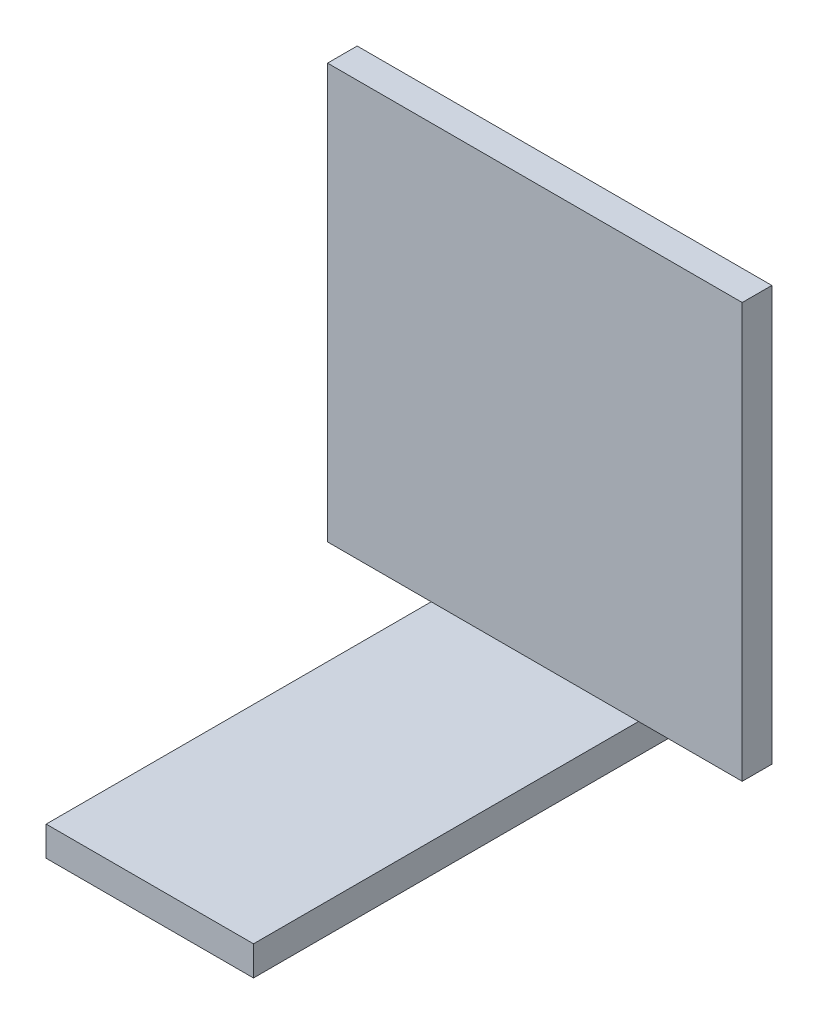
SolidWorks part; units mm, degrees
ref_plane "Front Plane" through (0, 0, 0) normal (0, 0, 1) x (1, 0, 0)
ref_plane "Top Plane" through (0, 0, 0) normal (0, 1, 0) x (1, 0, 0)
ref_plane "Right Plane" through (0, 0, 0) normal (1, 0, 0) x (0, 0, -1)
sketch "Sketch1" plane through (0, 0, 0) normal (0, 1, 0) x (1, 0, 0)
  line L1 (0, 0) -> (35, 0)
  line L2 (0, 0) -> (0, 70)
  line L3 (0, 70) -> (35, 70)
  line L4 (35, 0) -> (35, 70)
  dimension "D1" = 70
  dimension "D2" = 35
extrude "Boss-Extrude1" add sketch "Sketch1" along normal blind 5
sketch "Sketch2" plane through (0, 5, 0) normal (0, 1, 0) x (1, 0, 0)
  line L1 (52.5, 70) -> (-17.5, 70)
  line L2 (52.5, 70) -> (52.5, 65)
  line L3 (52.5, 65) -> (-17.5, 65)
  line L4 (-17.5, 70) -> (-17.5, 65)
  line L5 (17.5, -6.7649) -> (17.5, 87.4304) construction
  line L6 (35, 0) -> (35, 70) construction
  dimension "D1" = 5
  dimension "D2" = 70
  dimension "D3" = 17.5
extrude "Boss-Extrude2" add sketch "Sketch2" along normal blind 70
